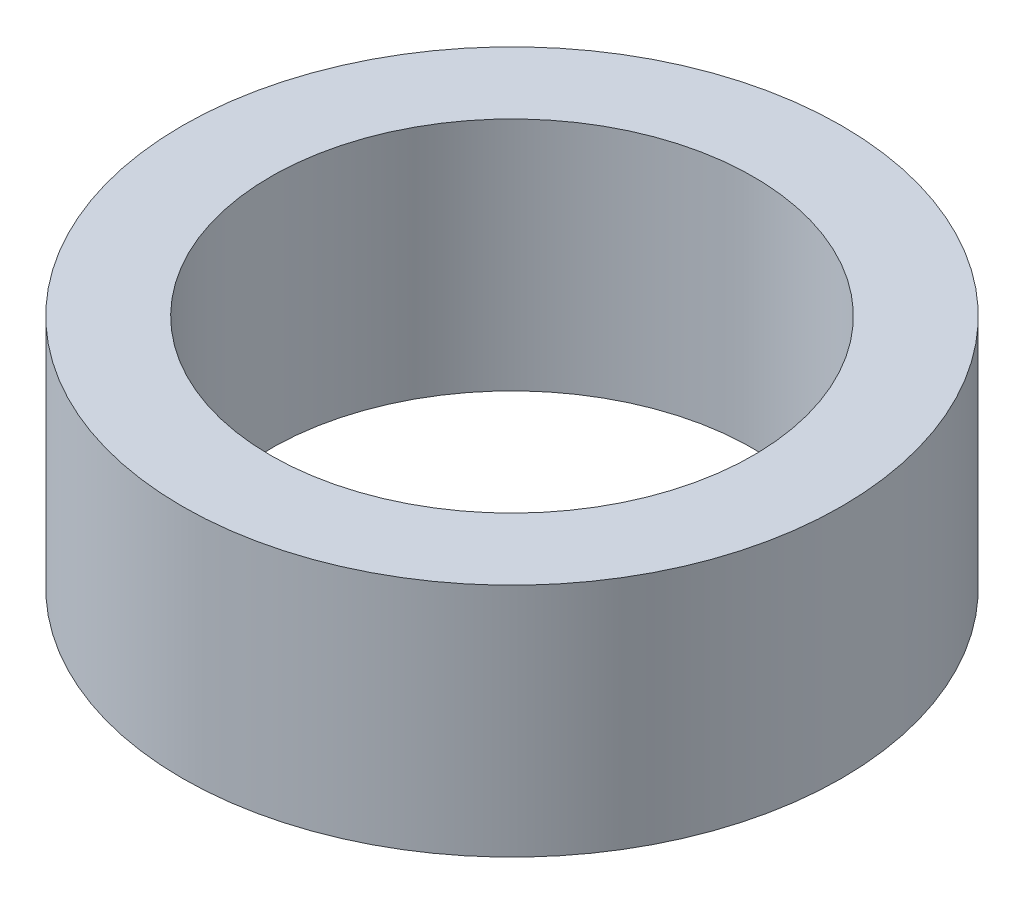
SolidWorks part; units mm, degrees
ref_plane "Ebene vorne" through (0, 0, 0) normal (0, 0, 1) x (1, 0, 0)
ref_plane "Ebene oben" through (0, 0, 0) normal (0, 1, 0) x (1, 0, 0)
ref_plane "Ebene rechts" through (0, 0, 0) normal (1, 0, 0) x (0, 0, -1)
sketch "Skizze1" plane through (0, 0, 0) normal (0, 1, 0) x (1, 0, 0)
  circle A0 centre (0, 0) radius 4.1
  circle A1 centre (0, 0) radius 5.6
  dimension "D1" = 8.2
  dimension "D2" = 11.2
extrude "Aufsatz-Linear austragen1" add sketch "Skizze1" along normal blind 4
